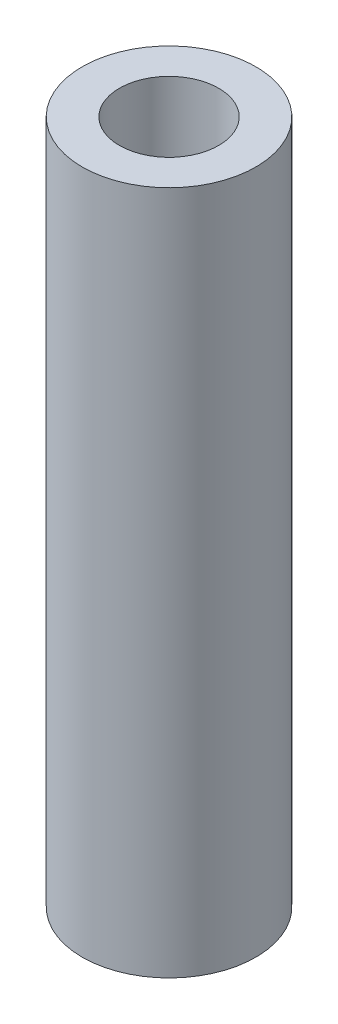
SolidWorks part; units mm, degrees
ref_plane "Front Plane" through (0, 0, 0) normal (0, 0, 1) x (1, 0, 0)
ref_plane "Top Plane" through (0, 0, 0) normal (0, 1, 0) x (1, 0, 0)
ref_plane "Right Plane" through (0, 0, 0) normal (1, 0, 0) x (0, 0, -1)
sketch "Sketch1" plane through (0, 0, 0) normal (0, 1, 0) x (1, 0, 0)
  circle A0 centre (0, 0) radius 2
  circle A1 centre (0, 0) radius 3.5
extrude "Boss-Extrude1" add sketch "Sketch1" along normal blind 27.58
